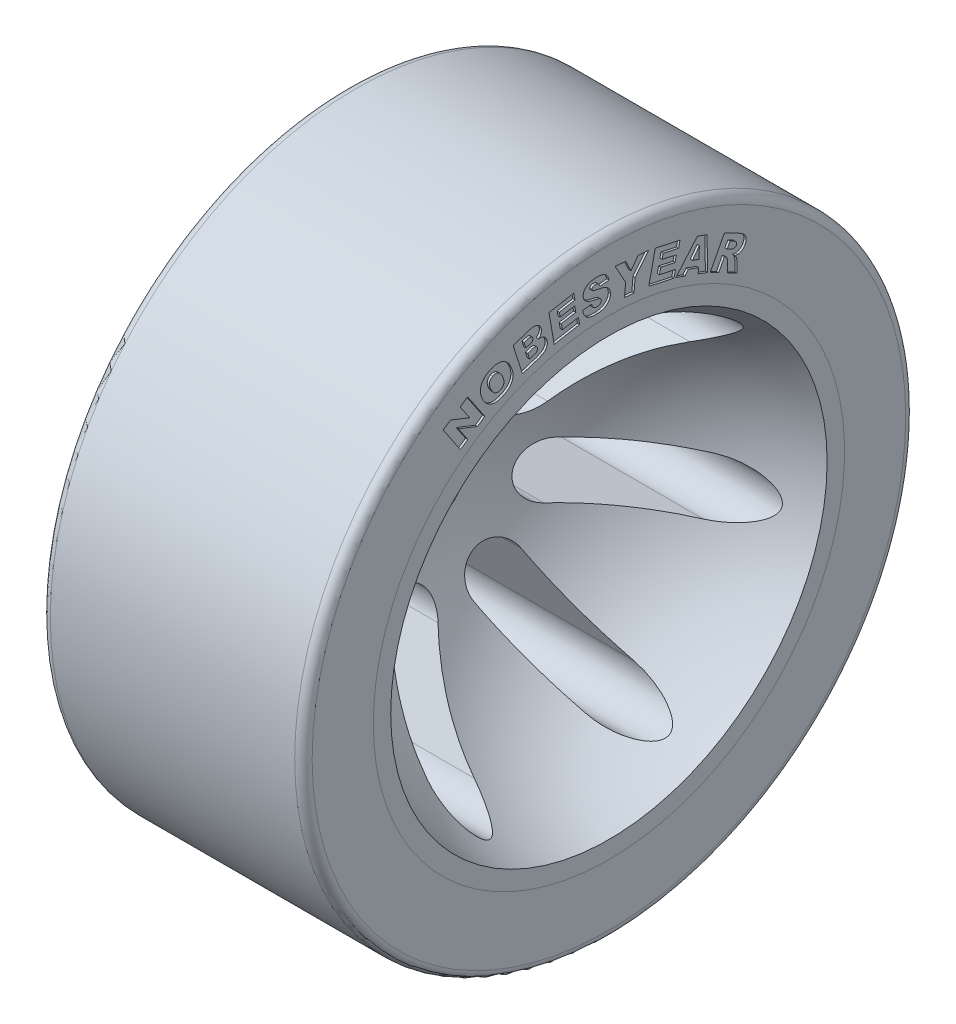
SolidWorks part; units mm, degrees
ref_plane "Front Plane" through (0, 0, 0) normal (0, 0, 1) x (1, 0, 0)
ref_plane "Top Plane" through (0, 0, 0) normal (0, 1, 0) x (1, 0, 0)
ref_plane "Right Plane" through (0, 0, 0) normal (1, 0, 0) x (0, 0, -1)
ref_axis "Axis1" through (-1.5, 0, 0) along (1, 0, 0)
sketch "Sketch1" plane through (0, 0, 0) normal (0, 0, 1) x (1, 0, 0)
  line L0 (0, 0) -> (10, 0)
  line L1 (30, 25) -> (30, 27)
  line L2 (30, 27) -> (0, 27)
  line L3 (0, 27) -> (0, 0)
  arc A0 (10, 0) -> (30, 25) centre (35, 0.5) cw
  dimension "D1" = 27
  dimension "D2" = 25
  dimension "D3" = 30
  dimension "D4" = 10
  dimension "D5" = 25
revolve "Hub" add sketch "Sketch1" angle 360 about L0
sketch "Sketch2" plane through (0, 0, 0) normal (0, 0, 1) x (1, 0, 0)
  line L0 (0, 27) -> (30, 27)
  line L1 (30, 27) -> (30, 35)
  line L14 (30, 35) -> (0, 35)
  line L15 (0, 35) -> (0, 27)
  point P4 (0, 0)
  point P6 (0, 0)
  point P7 (29.5679, 35)
  dimension "D1" = 8
revolve "Tire" add sketch "Sketch2" angle 360 about axis through (-1.5, 0, 0) along (1, 0, 0)
fillet "Fillet1" radius 1 2 edges at (0, 0, 35) (30, 0, 35)
sketch "Sketch3" plane through (0, 0, 0) normal (-1, 0, 0) x (0, 0, 1)
  circle A0 centre (0, 0) radius 7.5
  dimension "D1" = 15
extrude "Boss-Extrude1" add sketch "Sketch3" along normal blind 10 separate body
sketch "Sketch4" plane through (-10, 0, 0) normal (-1, 0, 0) x (0, 0, 1)
  circle A0 centre (0, 0) radius 3.175
  dimension "D1" = 6.35
extrude "Cut-Extrude1" cut sketch "Sketch4" against normal through all
sketch "Sketch5" plane through (0, 0, 0) normal (-1, 0, 0) x (0, 0, 1)
  line L0 (0, 11) -> (0, 21) construction
  line L1 (-3, 11) -> (-3, 21)
  line L2 (3, 11) -> (3, 21)
  arc A0 (-3, 11) -> (3, 11) centre (0, 11) ccw
  arc A1 (3, 21) -> (-3, 21) centre (0, 21) ccw
  point P3 (0, 16)
  dimension "D1" = 11
  dimension "D2" = 10
  dimension "D3" = 6
extrude "Cut-Extrude2" cut sketch "Sketch5" against normal through all
pattern_circular "CirPattern1" count 7 over 360 about axis through (0, 0, 0) along (1, 0, 0) of "Cut-Extrude2"
sketch "Sketch6" plane through (30, 0, 0) normal (1, 0, 0) x (0, 0, -1)
  arc A0 (-20.919, 18.6117) -> (18.6117, 20.919) centre (0, 0) cw construction
  text T0 "NOBESYEAR" font "Arial Black" height 3.5
  dimension "D1" = 28
extrude "Cut-Extrude3" cut sketch "Sketch6" against normal blind 0.25
